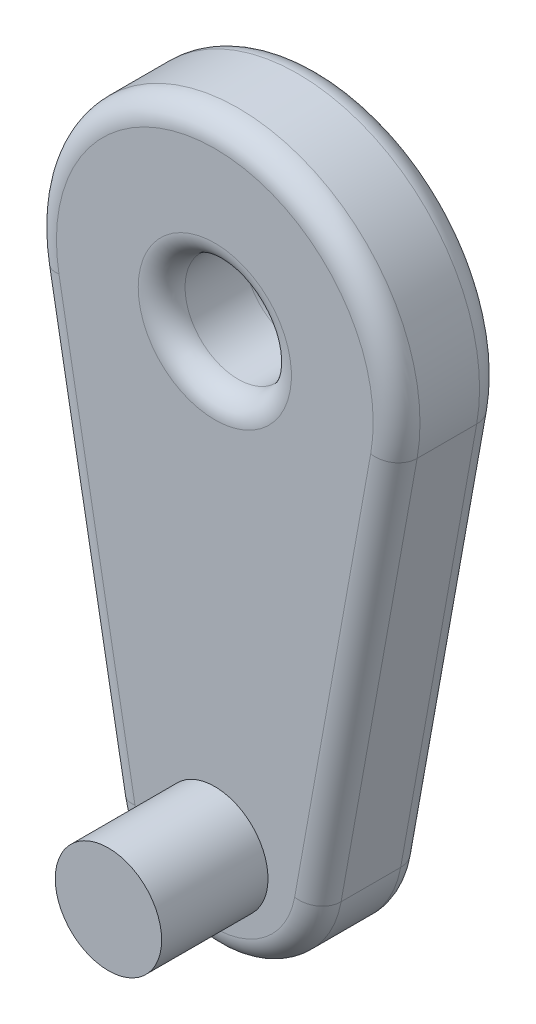
SolidWorks part; units mm, degrees
ref_plane "Front Plane" through (0, 0, 0) normal (0, 0, 1) x (1, 0, 0)
ref_plane "Top Plane" through (0, 0, 0) normal (0, 1, 0) x (1, 0, 0)
ref_plane "Right Plane" through (0, 0, 0) normal (1, 0, 0) x (0, 0, -1)
sketch "Sketch2" plane through (0, 0, 0) normal (0, 0, 1) x (1, 0, 0)
  line L1 (0, 7.9112) -> (0, -9.4931) construction
  line L3 (-8.4093, 1.685) -> (-4.836, -18.149)
  line L4 (8.4093, 1.685) -> (4.836, -18.149)
  arc A3 (-8.4093, 1.685) -> (8.4093, 1.685) centre (0, 3.1999) cw
  arc A4 (-4.836, -18.149) -> (4.836, -18.149) centre (0, -17.2777) ccw
  circle A5 centre (0, 3.1999) radius 2.5
  dimension "D1" = 5
extrude "Boss-Extrude1" add sketch "Sketch2" along normal blind 5
fillet "Fillet1" radius 1.1 10 edges at (-6.6227, -8.232, 0) (-6.6227, -8.232, 5) (2.5, 3.1999, 0) (0, -22.1916, 0) (6.6227, -8.232, 0) (0, 11.7446, 0) (2.5, 3.1999, 5) (6.6227, -8.232, 5) (0, -22.1916, 5) (0, 11.7446, 5)
sketch "Sketch5" plane through (0, 0, 5) normal (0, 0, 1) x (1, 0, 0)
  circle A0 centre (0, -17.826) radius 2.5
  dimension "D1" = 5
extrude "Boss-Extrude2" add sketch "Sketch5" along normal blind 5
